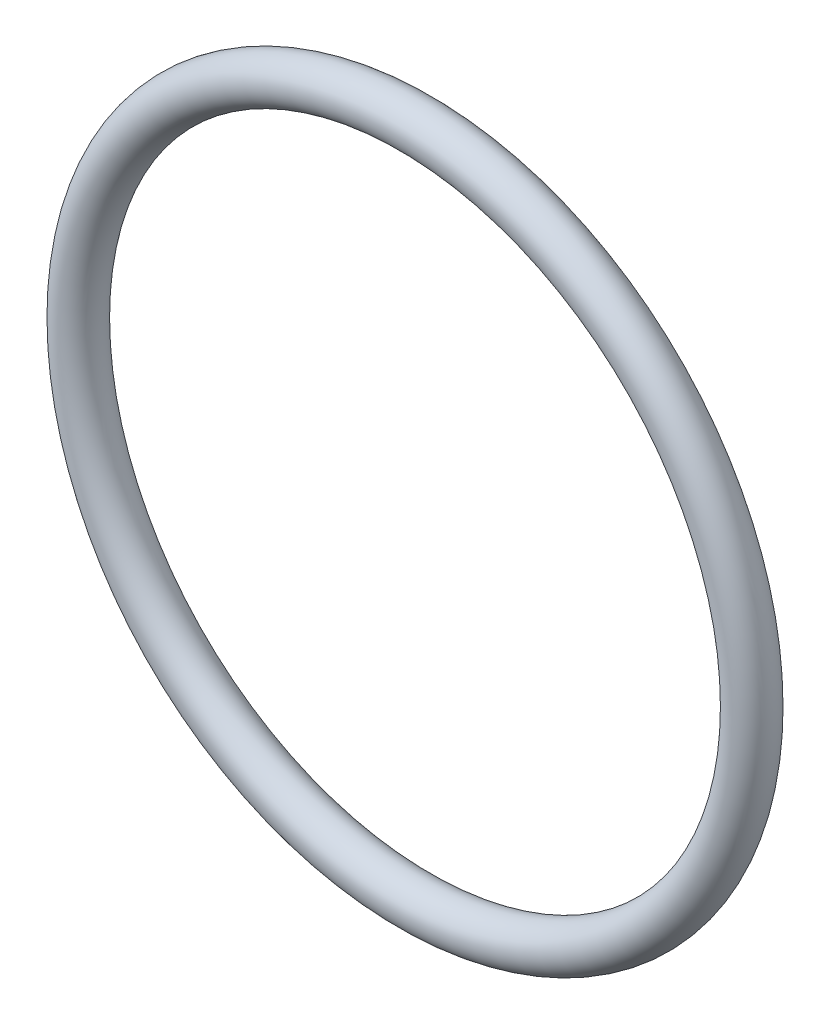
SolidWorks part; units mm, degrees
material "Rubber"
ref_plane "Front Plane" through (0, 0, 0) normal (0, 0, 1) x (1, 0, 0)
ref_plane "Top Plane" through (0, 0, 0) normal (0, 1, 0) x (1, 0, 0)
ref_plane "Right Plane" through (0, 0, 0) normal (1, 0, 0) x (0, 0, -1)
sketch "Sketch3" plane through (0, 0, 0) normal (0, 1, 0) x (1, 0, 0)
  line L0 (-24.13, 0) -> (24.13, 0) construction
  line L1 (0, 0) -> (0, 4.4002) construction
  line L2 (24.13, 0) -> (25.7175, 0) construction
  line L3 (24.13, 0) -> (22.5425, 0) construction
  circle A0 centre (24.13, 0) radius 1.5875
  point P3 (24.13, 0)
  point P4 (0, 0)
  dimension "D1" = 3.175
  dimension "D4" = 24.13
revolve "Revolve1" add sketch "Sketch3" angle 360 about L1
